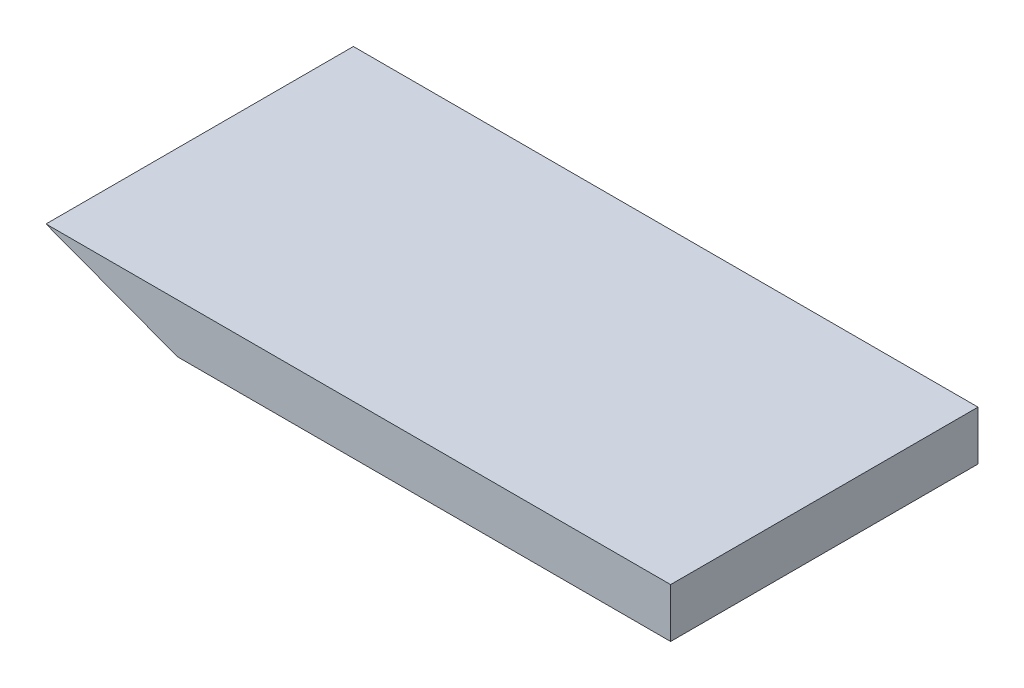
SolidWorks part; units mm, degrees
material "Rubber"
ref_plane "Front Plane" through (0, 0, 0) normal (0, 0, 1) x (1, 0, 0)
ref_plane "Top Plane" through (0, 0, 0) normal (0, 1, 0) x (1, 0, 0)
ref_plane "Right Plane" through (0, 0, 0) normal (1, 0, 0) x (0, 0, -1)
sketch "Sketch1" plane through (0, 0, 0) normal (0, 1, 0) x (1, 0, 0)
  line L1 (-19, 9.35) -> (19, 9.35)
  line L2 (-19, 9.35) -> (-19, -9.35)
  line L3 (-19, -9.35) -> (19, -9.35)
  line L4 (19, 9.35) -> (19, -9.35)
  line L5 (-19, 9.35) -> (19, -9.35) construction
  line L6 (-19, -9.35) -> (19, 9.35) construction
  point P0 (0, 0)
  dimension "D1" = 38
  dimension "D2" = 18.7
extrude "Boss-Extrude1" add sketch "Sketch1" along normal blind 3
sketch "Sketch2" plane through (0, 0, 9.35) normal (0, 0, 1) x (1, 0, 0)
  line L0 (-19, 3) -> (-19, 0)
  line L1 (-19, 0) -> (-11, 0)
  line L2 (-19, 0) -> (19, 0) construction
  line L3 (-11, 0) -> (-19, 3)
  dimension "D1" = 3
  dimension "D2" = 8
extrude "Cut-Extrude1" cut sketch "Sketch2" against normal through all both and the other way through all
